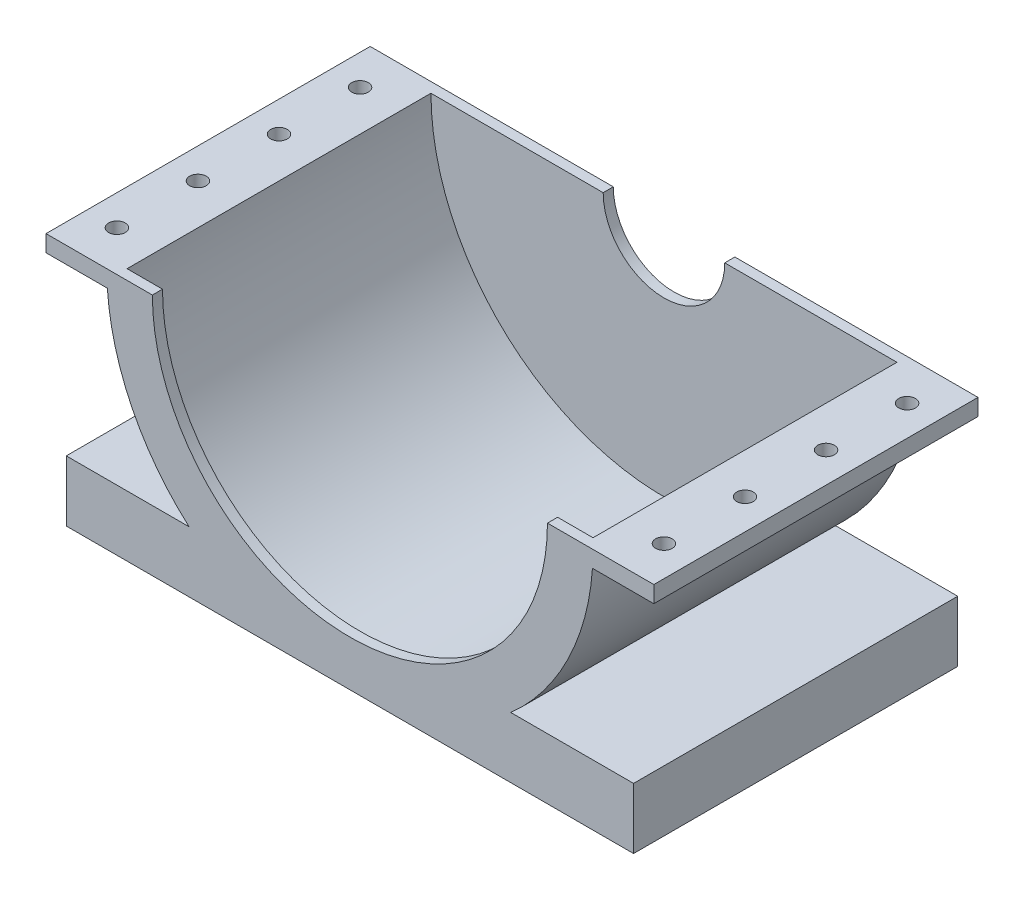
SolidWorks part; units mm, degrees
ref_plane "Front Plane" through (0, 0, 0) normal (0, 0, 1) x (1, 0, 0)
ref_plane "Top Plane" through (0, 0, 0) normal (0, 1, 0) x (1, 0, 0)
ref_plane "Right Plane" through (0, 0, 0) normal (1, 0, 0) x (0, 0, -1)
sketch "Sketch1" plane through (0, 0, 0) normal (0, 0, 1) x (1, 0, 0)
  line L0 (0, 0) -> (0, 60) construction
  line L1 (-70, 0) -> (70, 0)
  line L2 (-70, 0) -> (-70, 15)
  line L3 (-70, 15) -> (-39.6863, 15)
  line L4 (70, 0) -> (70, 15)
  line L5 (-75, 60) -> (-48.75, 60)
  line L6 (75, 60) -> (75, 55.9)
  line L7 (75, 55.9) -> (59.8598, 55.9)
  line L8 (-75, 55.9) -> (-75, 60)
  line L9 (48.75, 60) -> (75, 60)
  line L10 (-59.8598, 55.9) -> (-75, 55.9)
  line L11 (39.6863, 15) -> (70, 15)
  arc A0 (-59.8598, 55.9) -> (-39.6863, 15) centre (0, 60) ccw
  arc A1 (-48.75, 60) -> (48.75, 60) centre (0, 60) ccw
  arc A2 (39.6863, 15) -> (59.8598, 55.9) centre (0, 60) ccw
  point P4 (0, 0)
  point P12 (0, 60)
  point P19 (-17.5525, 4.0536)
  point P20 (-47.22, 15)
  point P21 (0, 60)
  point P22 (0, 60)
  point P23 (0, 60)
  point P24 (0, 60)
  point P25 (0, 0)
  dimension "D4" = 60
  dimension "D5" = 48.75
  dimension "D1" = 4.1
  dimension "D2" = 15
  dimension "D3" = 150
  dimension "D6" = 140
extrude "Boss-Extrude1" add sketch "Sketch1" along normal blind 80
sketch "Sketch3" plane through (0, 0, 0) normal (0, 0, -1) x (-1, 0, 0)
  line L0 (-48.75, 60) -> (-15, 60)
  line L1 (15, 60) -> (48.75, 60)
  line L11 (70, 0) -> (70, 15)
  line L12 (70, 15) -> (39.6863, 15)
  line L13 (59.8598, 55.9) -> (75, 55.9)
  line L14 (75, 55.9) -> (75, 60)
  line L15 (75, 60) -> (48.75, 60)
  line L16 (-48.75, 60) -> (-75, 60)
  line L17 (-75, 60) -> (-75, 55.9)
  line L18 (-75, 55.9) -> (-59.8598, 55.9)
  line L19 (-39.6863, 15) -> (-70, 15)
  line L20 (-70, 15) -> (-70, 0)
  line L21 (-70, 0) -> (70, 0)
  line L22 (70, 0) -> (70, 15)
  line L23 (70, 15) -> (39.6863, 15)
  line L24 (59.8598, 55.9) -> (75, 55.9)
  line L25 (75, 55.9) -> (75, 60)
  line L26 (75, 60) -> (48.75, 60)
  line L27 (-48.75, 60) -> (-75, 60)
  line L28 (-75, 60) -> (-75, 55.9)
  line L29 (-75, 55.9) -> (-59.8598, 55.9)
  line L30 (-39.6863, 15) -> (-70, 15)
  line L31 (-70, 15) -> (-70, 0)
  line L32 (-70, 0) -> (70, 0)
  arc A0 (-15, 60) -> (15, 60) centre (0, 60) ccw
  arc A3 (39.6863, 15) -> (59.8598, 55.9) centre (0, 60) ccw
  arc A4 (-48.75, 60) -> (48.75, 60) centre (0, 60) ccw
  arc A5 (-59.8598, 55.9) -> (-39.6863, 15) centre (0, 60) ccw
  arc A6 (39.6863, 15) -> (59.8598, 55.9) centre (0, 60) ccw
  arc A7 (-48.75, 60) -> (48.75, 60) centre (0, 60) ccw
  arc A8 (-59.8598, 55.9) -> (-39.6863, 15) centre (0, 60) ccw
  arc M21 (48.75, 60) -> (-48.75, 60) centre (0, 60) cw
  dimension "D2" = 15
  dimension "D1" = 0
extrude "Boss-Extrude2" add sketch "Sketch3" against normal blind 2.5 contours A0 L0 L1 M21
sketch "Sketch4" plane through (0, 60, 0) normal (0, 1, 0) x (1, 0, 0)
  line L0 (-75, -80) -> (-75, 0) construction
  line L1 (-48.75, -2.5) -> (-57.5, -2.5)
  line L2 (-48.75, -2.5) -> (-48.75, -77.5)
  line L3 (-48.75, -77.5) -> (-57.5, -77.5)
  line L4 (-57.5, -2.5) -> (-57.5, -77.5)
  line L5 (-48.75, -80) -> (-75, -80) construction
  line L6 (0, 0) -> (0, -102.9427) construction
  dimension "D1" = 17.5
  dimension "D2" = 2.5
revolve "Cut-Revolve1" cut sketch "Sketch4" angle 360 about L6
sketch "Sketch5" plane through (0, 60, 0) normal (0, 1, 0) x (1, 0, 0)
  line L0 (67.5, 0) -> (67.5, -80) construction
  line L1 (75, 0) -> (15, 0) construction
  line L2 (75, -80) -> (48.75, -80) construction
  line L3 (75, -80) -> (75, 0) construction
  line L4 (0, 0) -> (0, -77.5) construction
  line L5 (15, 0) -> (-15, 0) construction
  line L6 (57.5, -77.5) -> (-57.5, -77.5) construction
  line L7 (-67.5, 0) -> (-67.5, -80) construction
  circle A0 centre (67.5, -70) radius 2.05
  circle A1 centre (67.5, -50) radius 2.05
  circle A2 centre (67.5, -30) radius 2.05
  circle A3 centre (67.5, -10) radius 2.05
  circle A4 centre (-67.5, -10) radius 2.05
  circle A5 centre (-67.5, -30) radius 2.05
  circle A6 centre (-67.5, -50) radius 2.05
  circle A7 centre (-67.5, -70) radius 2.05
  dimension "D3" = 4.1
  dimension "D1" = 7.5
  dimension "D2" = 10
  dimension "D5" = 10
  dimension "D4" = 4
extrude "Cut-Extrude1" cut sketch "Sketch5" against normal up to surface (4.1 mm away) up to face at (-67.4299, 55.9, 40)
